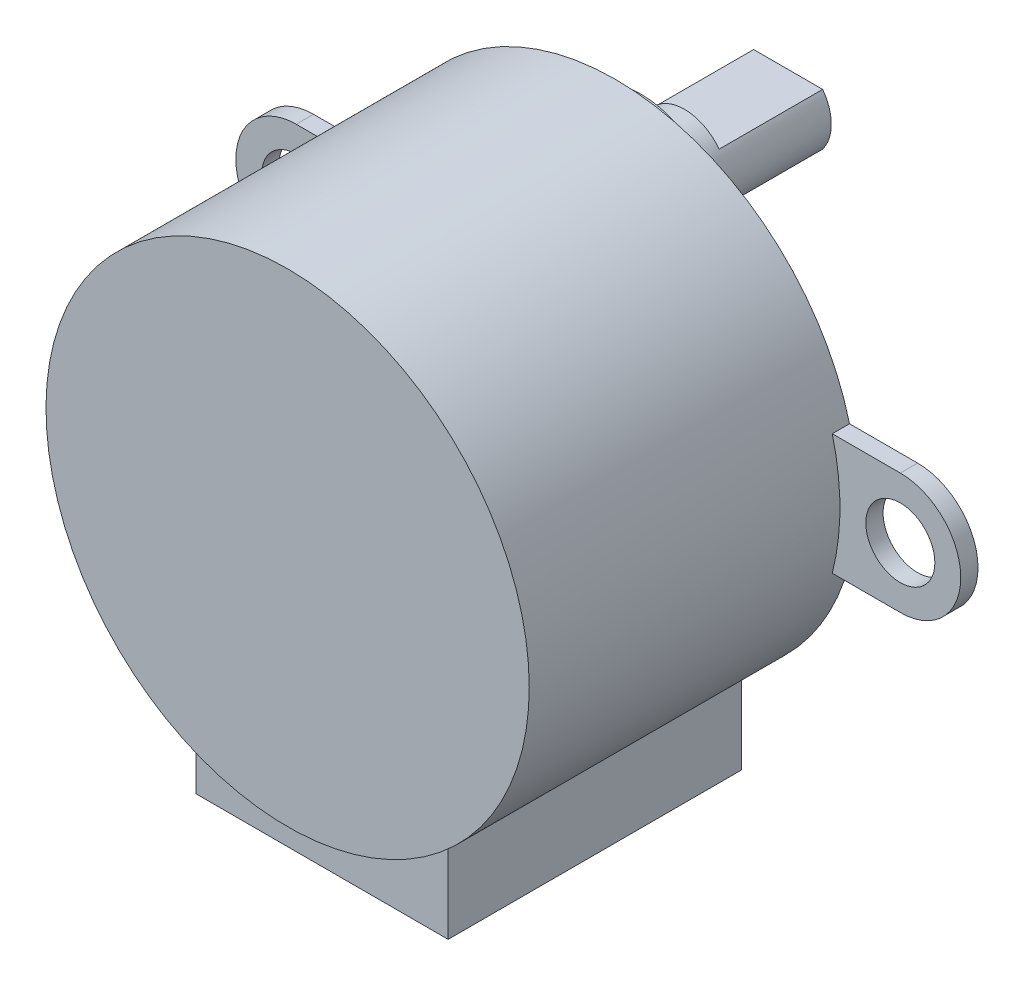
SolidWorks part; units mm, degrees
ref_plane "Front Plane" through (0, 0, 0) normal (0, 0, 1) x (1, 0, 0)
ref_plane "Top Plane" through (0, 0, 0) normal (0, 1, 0) x (1, 0, 0)
ref_plane "Right Plane" through (0, 0, 0) normal (1, 0, 0) x (0, 0, -1)
sketch "Sketch1" plane through (0, 0, 0) normal (0, 0, 1) x (1, 0, 0)
  line L0 (-17.5, 3.5) -> (-13.5554, 3.5)
  line L1 (-17.5, -3.5) -> (-13.5554, -3.5)
  line L2 (13.5554, 3.5) -> (17.5, 3.5)
  line L3 (13.5554, -3.5) -> (17.5, -3.5)
  line L4 (-7.3, -17) -> (7.3, -17)
  line L5 (-7.3, -17) -> (-7.3, -11.9461)
  line L6 (7.3, -17) -> (7.3, -11.9461)
  arc A0 (-13.5554, -3.5) -> (-7.3, -11.9461) centre (0, 0) ccw
  circle A1 centre (17.5, 0) radius 2
  circle A2 centre (-17.5, 0) radius 2
  arc A3 (17.5, -3.5) -> (17.5, 3.5) centre (17.5, 0) ccw
  arc A4 (-17.5, 3.5) -> (-17.5, -3.5) centre (-17.5, 0) ccw
  arc A5 (13.5554, 3.5) -> (-13.5554, 3.5) centre (0, 0) ccw
  arc A6 (7.3, -11.9461) -> (13.5554, -3.5) centre (0, 0) ccw
  point P16 (0, -17)
  dimension "D1" = 28
  dimension "D2" = 4
  dimension "D3" = 4
  dimension "D4" = 7
  dimension "D5" = 7
  dimension "D6" = 35
  dimension "D7" = 17.5
  dimension "D8" = 14.6
  dimension "D9" = 17
extrude "Boss-Extrude1" add sketch "Sketch1" along normal blind 1
sketch "Sketch2" plane through (0, 0, 1) normal (0, 0, 1) x (1, 0, 0)
  line L0 (-7.3, -11.9461) -> (-7.3, -17) construction
  line L1 (-7.3, -17) -> (7.3, -17) construction
  line L2 (7.3, -17) -> (7.3, -11.9461) construction
  line L3 (-7.3, -11.9461) -> (-7.3, -17)
  line L4 (-7.3, -17) -> (7.3, -17)
  line L5 (7.3, -17) -> (7.3, -11.9461)
  arc A0 (7.3, -11.9461) -> (13.5554, -3.5) centre (0, 0) ccw construction
  arc A1 (-13.5554, -3.5) -> (-7.3, -11.9461) centre (0, 0) ccw construction
  arc A2 (13.5554, 3.5) -> (-13.5554, 3.5) centre (0, 0) ccw construction
  arc A3 (7.3, -11.9461) -> (13.5554, -3.5) centre (0, 0) ccw
  arc A4 (-13.5554, -3.5) -> (-7.3, -11.9461) centre (0, 0) ccw
  arc A5 (13.5554, 3.5) -> (-13.5554, 3.5) centre (0, 0) ccw
  arc A6 (-13.5554, 3.5) -> (-13.5554, -3.5) centre (0, 0) ccw
  arc A7 (13.5554, 3.5) -> (13.5554, -3.5) centre (0, 0) cw
extrude "Boss-Extrude2" add sketch "Sketch2" along normal blind 18
sketch "Sketch3" plane through (0, 0, 19) normal (0, 0, 1) x (1, 0, 0)
  line L0 (7.3, -17) -> (7.3, -11.9461) construction
  line L1 (-7.3, -17) -> (7.3, -17) construction
  line L2 (-7.3, -11.9461) -> (-7.3, -17) construction
  line L3 (7.3, -17) -> (7.3, -11.9461)
  line L4 (-7.3, -17) -> (7.3, -17)
  line L5 (-7.3, -11.9461) -> (-7.3, -17)
  arc A0 (-7.3, -11.9461) -> (7.3, -11.9461) centre (0, 0) ccw
  arc A1 (7.3, -11.9461) -> (-7.3, -11.9461) centre (0, 0) ccw construction
extrude "Cut-Extrude1" cut sketch "Sketch3" against normal blind 2 and the other way through all
sketch "Sketch4" plane through (0, 0, 0) normal (0, 0, -1) x (-1, 0, 0)
  circle A0 centre (0, 8) radius 4.5
  dimension "D1" = 9
  dimension "D2" = 8
extrude "Boss-Extrude3" add sketch "Sketch4" along normal blind 1.5
sketch "Sketch5" plane through (0, 0, -1.5) normal (0, 0, -1) x (-1, 0, 0)
  circle A0 centre (0, 8) radius 2.5
  circle A1 centre (0, 8) radius 4.5 construction
  dimension "D1" = 5
extrude "Boss-Extrude4" add sketch "Sketch5" along normal blind 8.5
sketch "Sketch6" plane through (0, 0, -10) normal (0, 0, -1) x (-1, 0, 0)
  line L0 (-2, 9.5) -> (2, 9.5)
  line L1 (-2, 6.5) -> (2, 6.5)
  circle A0 centre (0, 8) radius 2.5 construction
  arc A1 (-2, 6.5) -> (2, 6.5) centre (0, 8) ccw
  arc A2 (2, 9.5) -> (-2, 9.5) centre (0, 8) ccw
  dimension "D1" = 1.5
  dimension "D2" = 1.5
extrude "Cut-Extrude2" cut sketch "Sketch6" against normal blind 6
